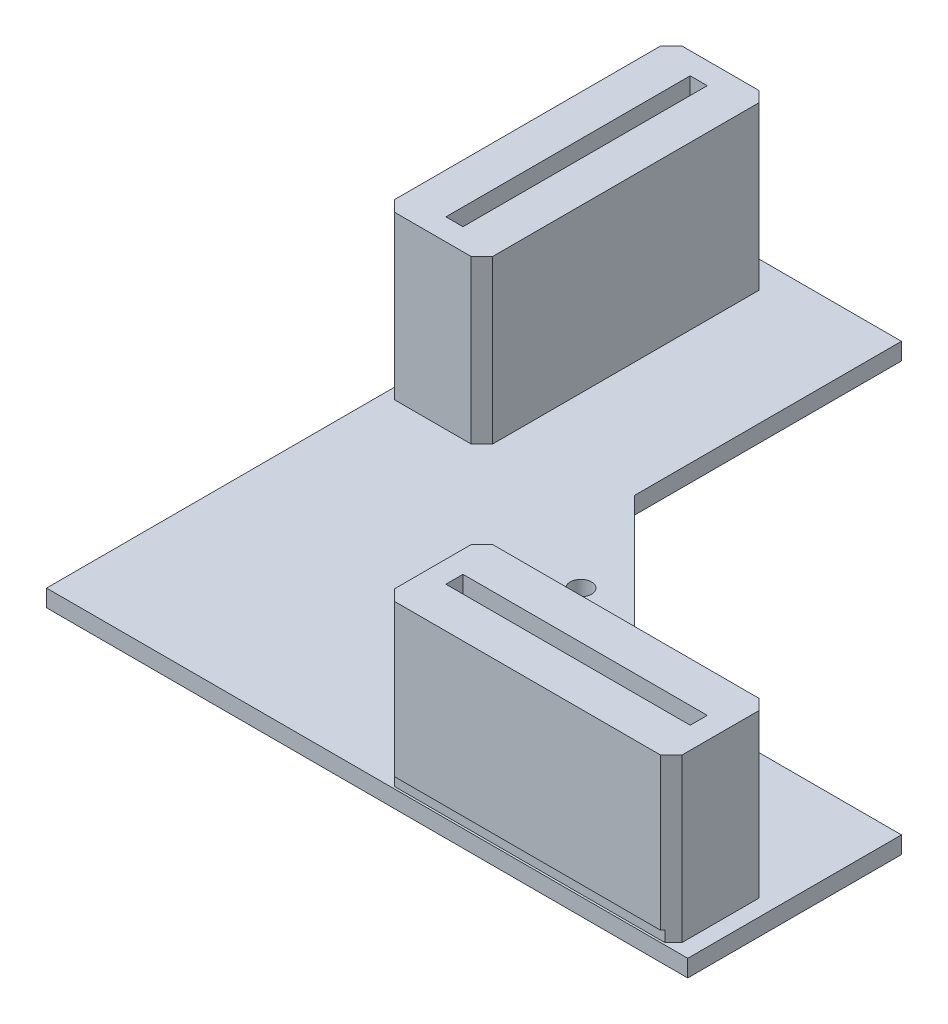
SolidWorks part; units mm, degrees
material "丙烯酸(中高冲击)"
ref_plane "前视基准面" through (0, 0, 0) normal (0, 0, 1) x (1, 0, 0)
ref_plane "上视基准面" through (0, 0, 0) normal (0, 1, 0) x (1, 0, 0)
ref_plane "右视基准面" through (0, 0, 0) normal (1, 0, 0) x (0, 0, -1)
other "Configuration Table"
sketch "草图2" plane through (0, 0, 0) normal (0, 1, 0) x (1, 0, 0)
  line L0 (-15, 0) -> (-15, 25)
  line L1 (0, 0) -> (-35, 0) construction
  line L2 (0, 0) -> (0, -35) construction
  line L3 (0, -35) -> (-35, -35)
  line L4 (-35, 0) -> (-35, -35)
  line L5 (-15, 25) -> (-35, 25)
  line L6 (-35, 25) -> (-35, 0)
  line L7 (0, -35) -> (25, -35)
  line L8 (25, -35) -> (25, -15)
  line L9 (25, -15) -> (0, -15)
  line L10 (0, -15) -> (-15, 0)
  dimension "D1" = 35
  dimension "D2" = 35
  dimension "D3" = 25
  dimension "D4" = 20
  dimension "D5" = 25
  dimension "D6" = 20
extrude "凸台-拉伸1" add sketch "草图2" along normal blind 1.6
sketch "草图3" plane through (0, 0, 0) normal (0, 1, 0) x (1, 0, 0)
  line L0 (-35, 25) -> (-35, 10) construction
  line L1 (-35, 25) -> (-35, -35) construction
  line L2 (-15, 25) -> (-35, 25) construction
  line L3 (-707.1068, -707.1068) -> (34648.2323, 34648.2323) construction
  line L4 (-35, 23.46) -> (-25.8, 23.46) construction
  line L5 (-35, 23.46) -> (-35, -3.46) construction
  line L6 (-35, -3.46) -> (-25.8, -3.46) construction
  line L7 (-25.8, 23.46) -> (-25.8, -3.46) construction
  line L8 (-34, -3.46) -> (-35, -2.46)
  line L9 (-26.8, -3.46) -> (-25.8, -2.46)
  line L10 (-34, 23.46) -> (-35, 22.46)
  line L11 (-26.8, 23.46) -> (-25.8, 22.46)
  line L12 (-34, -3.46) -> (-26.8, -3.46)
  line L13 (-25.8, -2.46) -> (-25.8, 22.46)
  line L14 (-34, 23.46) -> (-26.8, 23.46)
  line L15 (-35, 22.46) -> (-35, -2.46)
  line L16 (23.46, -25.8) -> (-3.46, -25.8) construction
  line L17 (-3.46, -35) -> (-3.46, -25.8) construction
  line L18 (23.46, -35) -> (-3.46, -35) construction
  line L19 (23.46, -35) -> (23.46, -25.8) construction
  line L20 (25, -35) -> (10, -35) construction
  line L21 (22.46, -35) -> (-2.46, -35)
  line L22 (23.46, -34) -> (23.46, -26.8)
  line L23 (-2.46, -25.8) -> (22.46, -25.8)
  line L24 (-3.46, -34) -> (-3.46, -26.8)
  line L25 (23.46, -26.8) -> (22.46, -25.8)
  line L26 (23.46, -34) -> (22.46, -35)
  line L27 (-3.46, -26.8) -> (-2.46, -25.8)
  line L28 (-3.46, -34) -> (-2.46, -35)
  point P11 (-35, 10)
  dimension "D1" = 15
  dimension "D2" = 26.92
  dimension "D3" = 9.2
  dimension "D4" = 1
  dimension "D5" = 1
  dimension "D6" = 1
  dimension "D7" = 1
  dimension "D8" = 1
  dimension "D9" = 1
  dimension "D10" = 1
  dimension "D11" = 1
extrude "凸台-拉伸2" add sketch "草图3" along normal blind 15.2 from surface at 1.6 starting at face at (-7.1429, 1.6, 7.1429)
sketch "草图5" plane through (0, 0, 0) normal (0, 0, 1) x (1, 0, 0)
  line L0 (-3.46, 16.8) -> (-3.46, 1.6) construction
  line L1 (23.46, 1.6) -> (-3.46, 1.6)
  line L2 (23.46, 1.6) -> (23.46, 2.6)
  line L3 (23.46, 2.6) -> (-3.46, 2.6)
  line L4 (-3.46, 1.6) -> (-3.46, 2.6)
  dimension "D1" = 1
extrude "切除-拉伸2" cut sketch "草图5" against normal blind 0.2 from surface at 35 starting at face at (2.5, 5, 35)
sketch "草图6" plane through (0, 0, 0) normal (1, 0, 0) x (0, 0, -1)
  line L0 (-3.46, 16.8) -> (-3.46, 1.6) construction
  line L1 (23.46, 1.6) -> (-3.46, 1.6)
  line L2 (23.46, 1.6) -> (23.46, 2.6)
  line L3 (23.46, 2.6) -> (-3.46, 2.6)
  line L4 (-3.46, 1.6) -> (-3.46, 2.6)
  dimension "D1" = 1
extrude "切除-拉伸3" cut sketch "草图6" along normal blind 0.2 from surface at -35 starting at face at (-35, 5, -2.5)
sketch "草图7" plane through (0, 0, 0) normal (0, 1, 0) x (1, 0, 0)
  line L0 (-707.1068, -707.1068) -> (34648.2323, 34648.2323) construction
  line L1 (-35, 22.46) -> (-35, -2.46) construction
  line L2 (-31.2, 21.43) -> (-29.6, 21.43)
  line L3 (-31.2, 21.43) -> (-31.2, -1.43)
  line L4 (-31.2, -1.43) -> (-29.6, -1.43)
  line L5 (-29.6, 21.43) -> (-29.6, -1.43)
  line L6 (-26.8, 23.46) -> (-34, 23.46) construction
  line L7 (21.43, -31.2) -> (21.43, -29.6)
  line L8 (-1.43, -31.2) -> (-1.43, -29.6)
  line L9 (21.43, -29.6) -> (-1.43, -29.6)
  line L10 (21.43, -31.2) -> (-1.43, -31.2)
  point P9 (-35, 10)
  point P10 (-31.2, 10)
  point P13 (-30.4, 23.46)
  point P14 (-30.4, 21.43)
  dimension "D1" = 22.86
  dimension "D2" = 1.6
extrude "切除-拉伸4" cut sketch "草图7" against normal blind 9 from surface at 16.8 starting at face at (-30.4, 16.8, -10)
sketch "草图8" plane through (0, 0, 0) normal (0, 1, 0) x (1, 0, 0)
  line L1 (-35, -35) -> (-10, -35) construction
  line L2 (-35, -35) -> (-35, -10) construction
  line L3 (-35, -10) -> (-10, -10) construction
  line L4 (-10, -35) -> (-10, -10) construction
  circle A0 centre (-10, -10) radius 1
  dimension "D3" = 2
  dimension "D1" = 25
  dimension "D2" = 25
extrude "切除-拉伸5" cut sketch "草图8" against normal up to surface (1.6 mm away) from surface at 1.6 up to face at (-7.1429, 0, 7.1429) starting at face at (-7.1429, 1.6, 7.1429)
